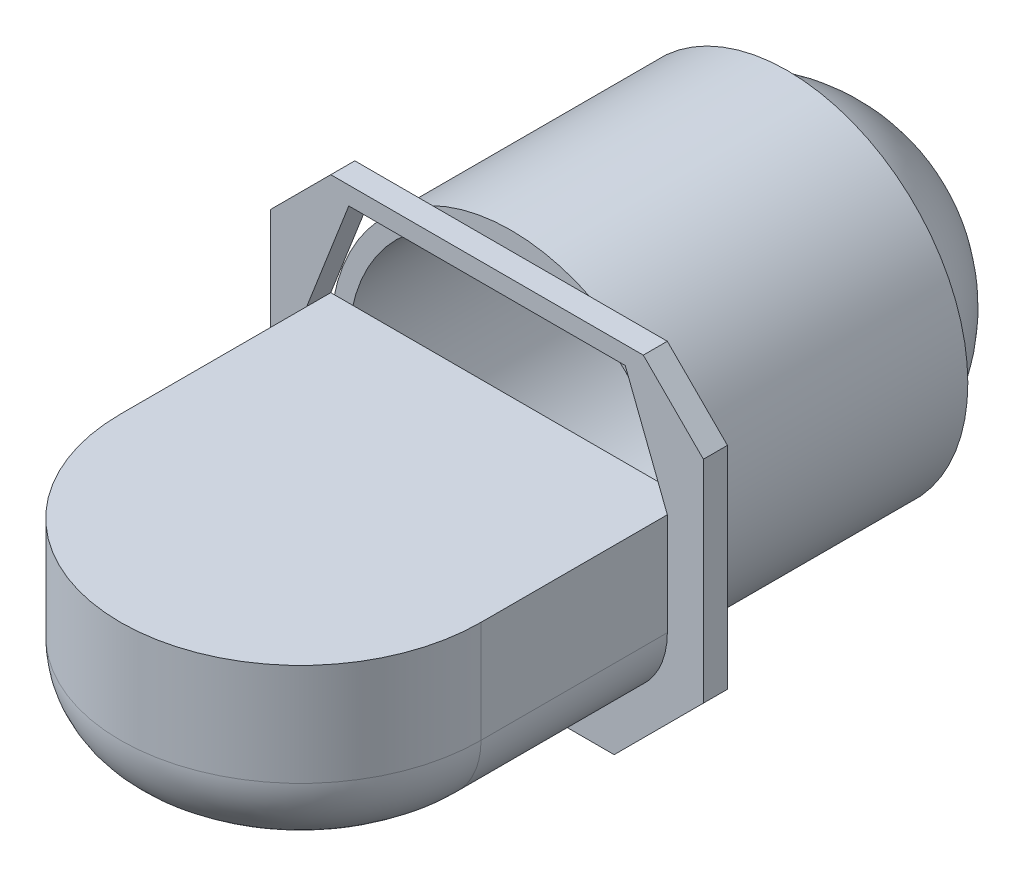
SolidWorks part; units mm, degrees
ref_plane "Спереди" through (0, 0, 0) normal (0, 0, 1) x (1, 0, 0)
ref_plane "Сверху" through (0, 0, 0) normal (0, 1, 0) x (1, 0, 0)
ref_plane "Справа" through (0, 0, 0) normal (1, 0, 0) x (0, 0, -1)
other "Configuration Table"
sketch "Sketch1" plane through (0, 0, 0) normal (0, 0, 1) x (1, 0, 0)
  circle A0 centre (0, 0) radius 30
  circle A1 centre (0, 0) radius 27
  dimension "D1" = 60
  dimension "D2" = 3
extrude "Boss-Extrude1" add sketch "Sketch1" along normal blind 46
sketch "Sketch3" plane through (0, 0, 0) normal (0, 1, 0) x (1, 0, 0)
  line L1 (27, 0) -> (0, 0)
  line L2 (0, 0) -> (0, 20)
  line L3 (0, 24.3239) -> (0, -4.1272) construction
  arc A0 (0, 20) -> (27, 0) centre (0, -8.225) cw
  dimension "D1" = 20
revolve "Revolve1" add sketch "Sketch3" angle 360 about L3
sketch "Sketch5" plane through (0, 0, 0) normal (0, 1, 0) x (1, 0, 0)
  line L0 (0, 31.462) -> (0, -103.4558) construction
  line L1 (-30, -46) -> (-30, -81)
  line L2 (-30, -46) -> (30, -46) construction
  line L3 (30, -81) -> (30, -46)
  line L4 (30, -46) -> (-30, -46)
  arc A0 (-30, -81) -> (30, -81) centre (0, -81) ccw
  dimension "D1" = 60
  dimension "D2" = 35
extrude "Boss-Extrude2" add sketch "Sketch5" along normal blind 6 and the other way blind 24 separate body
fillet "Fillet1" radius 13 3 edges at (30, -24, 63.5) (0, -24, 111) (-30, -24, 63.5)
sketch "Sketch7" plane through (0, 0, 46) normal (0, 0, 1) x (1, 0, 0)
  line L0 (-36, 17) -> (-36, -18.1508)
  line L1 (-36, -18.1508) -> (-21.1508, -33)
  line L2 (-21.1508, -33) -> (21.1508, -33)
  line L3 (21.1508, -33) -> (36, -18.1508)
  line L4 (36, -18.1508) -> (36, 17)
  line L5 (36, 17) -> (26, 27)
  line L6 (26, 27) -> (-26, 27)
  line L7 (-26, 27) -> (-36, 17)
  line L8 (0, 40.4452) -> (0, -48.0985) construction
  line L9 (-30, 6) -> (30, 6)
  line L10 (30, 6) -> (23, 24)
  line L11 (23, 24) -> (-23, 24)
  line L12 (-23, 24) -> (-30, 6)
  circle A0 centre (0, 0) radius 27 construction
  dimension "D1" = 6
  dimension "D2" = 18
  dimension "D3" = 46
  dimension "D4" = 52
  dimension "D5" = 60
  dimension "D6" = 45
  dimension "D7" = 21
extrude "Boss-Extrude7" add sketch "Sketch7" along normal blind 4
